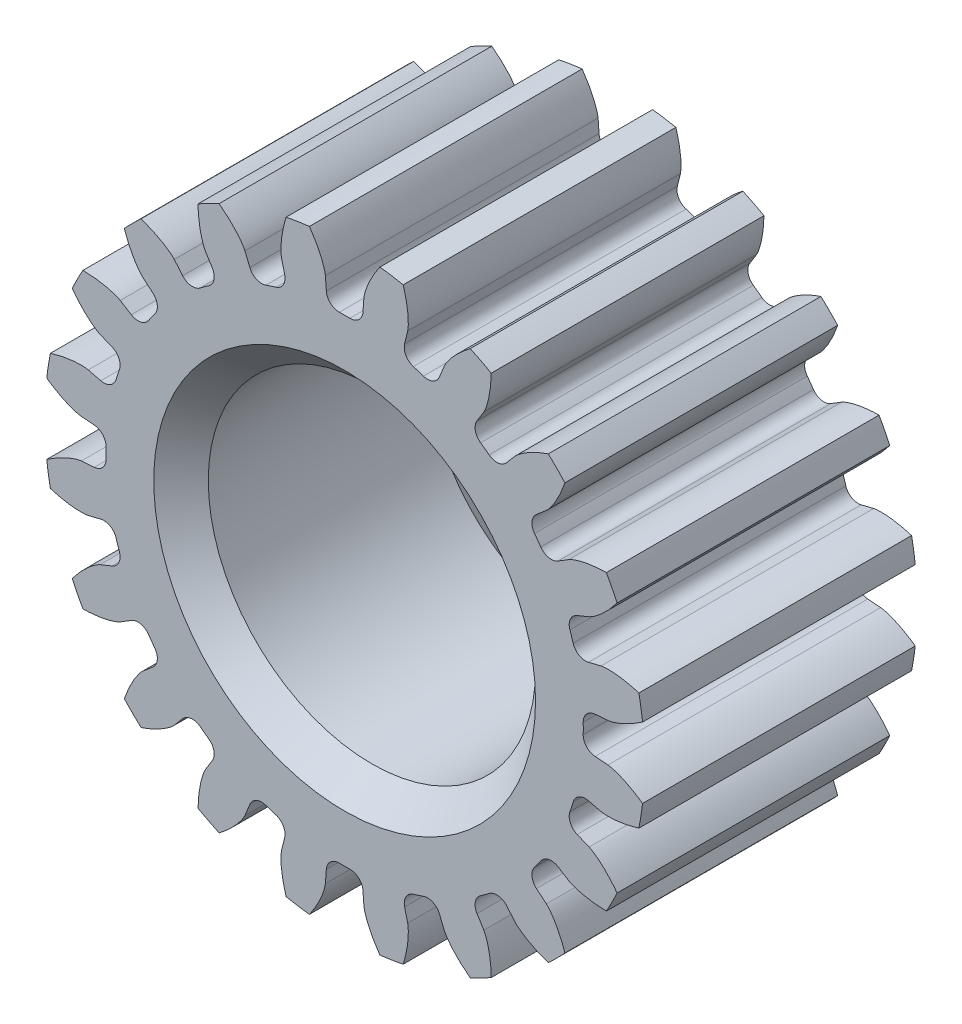
SolidWorks part; units mm, degrees
ref_plane "Front Plane" through (0, 0, 0) normal (0, 0, 1) x (1, 0, 0)
ref_plane "Top Plane" through (0, 0, 0) normal (0, 1, 0) x (1, 0, 0)
ref_plane "Right Plane" through (0, 0, 0) normal (1, 0, 0) x (0, 0, -1)
sketch "Sketch1" plane through (0, 0, 0) normal (0, 0, 1) x (1, 0, 0)
  circle A0 centre (0, 0) radius 6.985
extrude "BodyBlank" add sketch "Sketch1" along normal blind 6.35
ref_plane "CirclesPlane" through (0, 0, 6.35) normal (0, 0, 1) x (1, 0, 0)
sketch "EqDrivenInvoluteCurves" plane through (0, 0, 6.35) normal (0, 0, 1) x (1, 0, 0)
  line L0 (0, 0) -> (5.5415, 0.4052) construction
  line L1 (5.5415, -0.4052) -> (0, 0) construction
  line L2 (5.8308, 0.4264) -> (6.1314, 0.4484)
  line L3 (5.8308, -0.4264) -> (6.1314, -0.4484)
  circle A0 centre (0, 0) radius 5.5562 construction
  circle A1 centre (0, 0) radius 6.1477 construction
  circle A2 centre (0, 0) radius 6.35 construction
  circle A3 centre (0, 0) radius 6.985 construction
  arc A4 (6.9367, 0.8204) -> (6.9367, -0.8204) centre (0, 0) cw
  arc A5 (5.5549, 0.1229) -> (5.5549, -0.1229) centre (0, 0) cw
  arc A6 (5.8308, 0.4264) -> (5.5549, 0.1229) centre (5.8525, 0.1295) ccw
  arc A7 (5.5549, -0.1229) -> (5.8308, -0.4264) centre (5.8525, -0.1295) ccw
  spline S0 degree 4 poles (6.1314, 0.4484) (6.1327, 0.4485) (6.1364, 0.4488) (6.1433, 0.4497) (6.1547, 0.4514) (6.1691, 0.4539) (6.1877, 0.4576) (6.2095, 0.4625) (6.2334, 0.4684) (6.2593, 0.4756) (6.2851, 0.4833) (6.3108, 0.4915) (6.3363, 0.5001) (6.367, 0.5112) (6.4038, 0.5252) (6.4466, 0.5426) (6.4949, 0.5638) (6.5438, 0.5868) (6.5918, 0.6106) (6.6399, 0.6359) (6.6863, 0.6614) (6.7341, 0.6892) (6.7782, 0.7156) (6.8272, 0.7467) (6.8666, 0.7722) (6.9182, 0.8074) (6.9486, 0.8287) (6.984, 0.8541) (6.9996, 0.8657) (7.0093, 0.8728) knots 0 0 0 0 0 0.005377 0.015084 0.028532 0.04661 0.064855 0.092111 0.119476 0.146842 0.174209 0.201575 0.228941 0.256307 0.307035 0.361767 0.4165 0.471232 0.525964 0.580697 0.635429 0.690161 0.744894 0.799626 0.854358 0.909091 0.954545 1 1 1 1 1 construction
  spline S1 degree 4 poles (6.1314, 0.4484) (6.1327, 0.4485) (6.1364, 0.4488) (6.1433, 0.4497) (6.1547, 0.4514) (6.1691, 0.4539) (6.1877, 0.4576) (6.2095, 0.4625) (6.2334, 0.4684) (6.2593, 0.4756) (6.2851, 0.4833) (6.3108, 0.4915) (6.3363, 0.5001) (6.367, 0.5112) (6.4038, 0.5252) (6.4466, 0.5426) (6.4949, 0.5638) (6.5438, 0.5868) (6.5918, 0.6106) (6.6399, 0.6359) (6.6863, 0.6614) (6.7341, 0.6892) (6.7782, 0.7156) (6.8272, 0.7467) (6.8666, 0.7722) (6.907, 0.7997) (6.9266, 0.8134) (6.9367, 0.8204) knots 0 0 0 0 0 0.005377 0.015084 0.028532 0.04661 0.064855 0.092111 0.119476 0.146842 0.174209 0.201575 0.228941 0.256307 0.307035 0.361767 0.4165 0.471232 0.525964 0.580697 0.635429 0.690161 0.744894 0.799626 0.854358 0.909091 0.909091 0.909091 0.909091 0.909091
  spline S2 degree 4 poles (6.1314, -0.4484) (6.1327, -0.4485) (6.1364, -0.4488) (6.1433, -0.4497) (6.1547, -0.4514) (6.1691, -0.4539) (6.1877, -0.4576) (6.2095, -0.4625) (6.2334, -0.4684) (6.2593, -0.4756) (6.2851, -0.4833) (6.3108, -0.4915) (6.3363, -0.5001) (6.367, -0.5112) (6.4038, -0.5252) (6.4466, -0.5426) (6.4949, -0.5638) (6.5438, -0.5868) (6.5918, -0.6106) (6.6399, -0.6359) (6.6863, -0.6614) (6.7341, -0.6892) (6.7782, -0.7156) (6.8272, -0.7467) (6.8666, -0.7722) (6.9182, -0.8074) (6.9486, -0.8287) (6.984, -0.8541) (6.9996, -0.8657) (7.0093, -0.8728) knots 0 0 0 0 0 0.005377 0.015084 0.028532 0.04661 0.064855 0.092111 0.119476 0.146842 0.174209 0.201575 0.228941 0.256307 0.307035 0.361767 0.4165 0.471232 0.525964 0.580697 0.635429 0.690161 0.744894 0.799626 0.854358 0.909091 0.954545 1 1 1 1 1 construction
  spline S3 degree 4 poles (6.1314, -0.4484) (6.1327, -0.4485) (6.1364, -0.4488) (6.1433, -0.4497) (6.1547, -0.4514) (6.1691, -0.4539) (6.1877, -0.4576) (6.2095, -0.4625) (6.2334, -0.4684) (6.2593, -0.4756) (6.2851, -0.4833) (6.3108, -0.4915) (6.3363, -0.5001) (6.367, -0.5112) (6.4038, -0.5252) (6.4466, -0.5426) (6.4949, -0.5638) (6.5438, -0.5868) (6.5918, -0.6106) (6.6399, -0.6359) (6.6863, -0.6614) (6.7341, -0.6892) (6.7782, -0.7156) (6.8272, -0.7467) (6.8666, -0.7722) (6.907, -0.7997) (6.9266, -0.8134) (6.9367, -0.8204) knots 0 0 0 0 0 0.005377 0.015084 0.028532 0.04661 0.064855 0.092111 0.119476 0.146842 0.174209 0.201575 0.228941 0.256307 0.307035 0.361767 0.4165 0.471232 0.525964 0.580697 0.635429 0.690161 0.744894 0.799626 0.854358 0.909091 0.909091 0.909091 0.909091 0.909091
  dimension "D5" = 0.2977
extrude "ToothCutMaster" cut sketch "EqDrivenInvoluteCurves" against normal through all
pattern_circular "ToothCutsPattern" count 20 over 360 about axis through (0, 0, 6.35) along (0, 0, -1) of "ToothCutMaster"
sketch "Sketch2" plane through (0, 0, 6.35) normal (0, 0, 1) x (1, 0, 0)
  circle A0 centre (0, 0) radius 3.81
  dimension "D1" = 7.62
extrude "Cut-Extrude1" cut sketch "Sketch2" against normal through all
chamfer "Chamfer1" distance 0.635 angle 45 2 edges at (3.81, 0, 0) (3.81, 0, 6.35)
equation "\"DiametralPitch\"= 40"
equation "\"NumTeeth\"= 20"
equation "\"FaceWidth\"=0.25"
equation "\"PressureAngle\"= 14.5deg'Default: 14.5"
equation "\"Addendum\"= 1 / \"DiametralPitch\""
equation "\"Dedendum\"= 1.25 / \"DiametralPitch\""
equation "\"WorkingDepth\"= 2 / \"DiametralPitch\""
equation "\"WholeDepth\"= 2.25 / \"DiametralPitch\""
equation "\"Clearance\"= 0.25 / \"DiametralPitch\""
equation "\"ToothThickness\"= 1.5708 / \"DiametralPitch\""
equation "\"CircularPitch\"= pi / \"DiametralPitch\""
equation "\"PitchCircle\"= \"NumTeeth\" / \"DiametralPitch\""
equation "\"OutsideDiameter\"= ( \"NumTeeth\" + 2 ) / \"DiametralPitch\""
equation "\"Fillet\"= \"Clearance\" * cos ( \"PressureAngle\" ) * tan ( ( 90 + \"PressureAngle\" ) / 2 )"
equation "\"AddendumCircle\"= \"PitchCircle\" + ( 2 * \"Addendum\" )"
equation "\"DedendumCircle\"= \"PitchCircle\" - ( 2 * \"Dedendum\" )"
equation "\"BaseCircle\"= \"PitchCircle\" * cos ( \"PressureAngle\" )"
equation "\"PitchAngle\"= 360deg / \"NumTeeth\""
equation "\"Alpha\"= sqr ( \"PitchCircle\" ^ 2 - \"BaseCircle\" ^ 2 ) / \"BaseCircle\" * 180 / PI - \"PressureAngle\""
equation "\"Beta\"= ( \"PitchAngle\" / 4 - \"Alpha\" )"
equation "\"Phi\"= sqr ( ( \"AddendumCircle\" / 2 ) ^ 2 - ( \"BaseCircle\" / 2 ) ^ 2 ) / ( \"BaseCircle\" / 2 )"
equation "\"D1@Sketch1\"=\"OutsideDiameter\""
equation "\"D1@BodyBlank\" = \"FaceWidth\""
equation "\"D1@EqDrivenInvoluteCurves\" = \"OutsideDiameter\""
equation "\"D2@EqDrivenInvoluteCurves\" = \"PitchCircle\""
equation "\"D3@EqDrivenInvoluteCurves\" = \"BaseCircle\""
equation "\"D4@EqDrivenInvoluteCurves\" = \"DedendumCircle\""
equation "\"D1@ToothCutsPattern\"=\"NumTeeth\""
